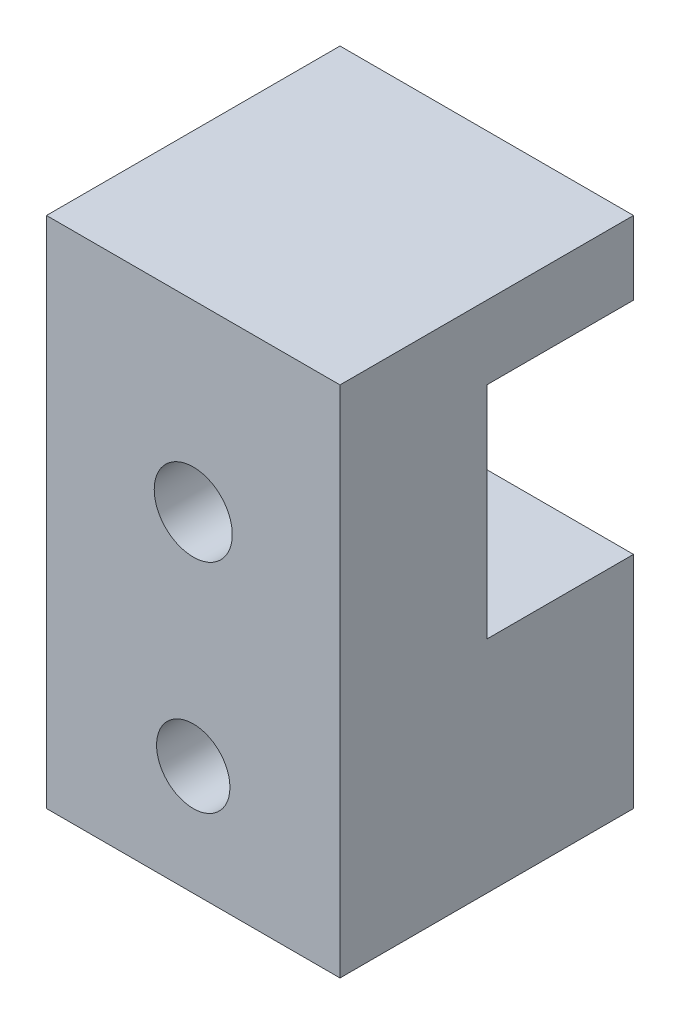
SolidWorks part; units mm, degrees
ref_plane "Front Plane" through (0, 0, 0) normal (0, 0, 1) x (1, 0, 0)
ref_plane "Top Plane" through (0, 0, 0) normal (0, 1, 0) x (1, 0, 0)
ref_plane "Right Plane" through (0, 0, 0) normal (1, 0, 0) x (0, 0, -1)
sketch "Sketch1" plane through (0, 0, 0) normal (0, 0, 1) x (1, 0, 0)
  line L1 (-12.7, -22.225) -> (12.7, -22.225)
  line L2 (-12.7, -22.225) -> (-12.7, 22.225)
  line L3 (-12.7, 22.225) -> (12.7, 22.225)
  line L4 (12.7, -22.225) -> (12.7, 22.225)
  line L5 (-12.7, -22.225) -> (12.7, 22.225) construction
  line L6 (-12.7, 22.225) -> (12.7, -22.225) construction
  point P0 (0, 0)
  dimension "D1" = 25.4
  dimension "D2" = 44.45
extrude "Boss-Extrude1" add sketch "Sketch1" along normal mid plane 25.4 contours L3 L4 L1 L2
sketch "Sketch2" plane through (0, 0, -12.7) normal (0, 0, -1) x (-1, 0, 0)
  line L0 (0, 55) -> (0, -55) construction
  line L1 (-12.7, -3.175) -> (12.7, -3.175)
  line L2 (-12.7, -3.175) -> (-12.7, 15.875)
  line L3 (-12.7, 15.875) -> (12.7, 15.875)
  line L4 (12.7, -3.175) -> (12.7, 15.875)
  line L5 (-12.7, -3.175) -> (12.7, 15.875) construction
  line L6 (-12.7, 15.875) -> (12.7, -3.175) construction
  line L7 (12.7, -22.225) -> (12.7, 22.225) construction
  line L8 (12.7, 22.225) -> (-12.7, 22.225) construction
  point P0 (0, 6.35)
  dimension "D1" = 15.875
  dimension "D2" = 19.05
extrude "Cut-Extrude1" cut sketch "Sketch2" against normal blind 12.7
sketch "Sketch3" plane through (0, 0, 12.7) normal (0, 0, 1) x (1, 0, 0)
  line L0 (0, -13.97) -> (0, 13.97) construction
  line L1 (-12.7, -22.225) -> (12.7, -22.225) construction
  circle A0 centre (0, -12.7) radius 3.175
  dimension "D1" = 6.35
  dimension "D2" = 9.525
extrude "Cut-Extrude2" cut sketch "Sketch3" against normal through all
sketch "Sketch4" plane through (0, 0, 0) normal (0, 0, -1) x (-1, 0, 0)
  line L0 (0, 13.97) -> (0, -13.97) construction
  line L1 (12.7, 15.875) -> (-12.7, 15.875) construction
  point P0 (0, 6.35)
  dimension "D1" = 9.525
hole_wizard "1/4 Clearance Hole1" positions "Sketch5" profile "Sketch7" hole size "1/4" standard "ANSI Inch" end condition through all
sketch "Sketch5" plane through (0, 0, 0) normal (0, 0, -1) x (-1, 0, 0)
  point P0 (0, 6.35)
sketch "Sketch7" plane through (0, 6.35, 0) normal (1, 0, 0) x (0, 1, 0)
  line L0 (0, 0) -> (0, 12.7)
  line L1 (0, 12.7) -> (3.3782, 12.7)
  line L2 (3.3782, 12.7) -> (3.3782, 0)
  line L5 (3.3782, 0) -> (0, 0)
  line L11 (0, -6.35) -> (0, 107.95) construction
  dimension "Thru Hole Dia." = 6.7564
  dimension "Thru Hole Depth" = 12.7
sketch "Sketch8" plane through (0, -22.225, 0) normal (0, -1, 0) x (1, 0, 0)
  point P0 (0, 0)
hole_wizard "#6-32 Tapped Hole1" positions "Sketch9" profile "Sketch11" tap size "#6-32" standard "ANSI Inch"
sketch "Sketch9" plane through (0, -22.225, 0) normal (0, -1, 0) x (-1, 0, 0)
  point P0 (0, 0)
sketch "Sketch11" plane through (0, -22.225, 0) normal (1, 0, 0) x (0, 0, -1)
  line L0 (0, 0) -> (0, 6.35)
  line L1 (0, 6.35) -> (1.3525, 6.35)
  line L2 (1.3525, 6.35) -> (1.3525, 0)
  line L5 (1.3525, 0) -> (0, 0)
  line L11 (0, -6.35) -> (0, 107.95) construction
  dimension "Thru Tap Drill Dia." = 2.7051
  dimension "Thru Tap Drill Depth" = 6.35
cosmetic thread "Hole Thread1" parameters "D2"=3.5052
